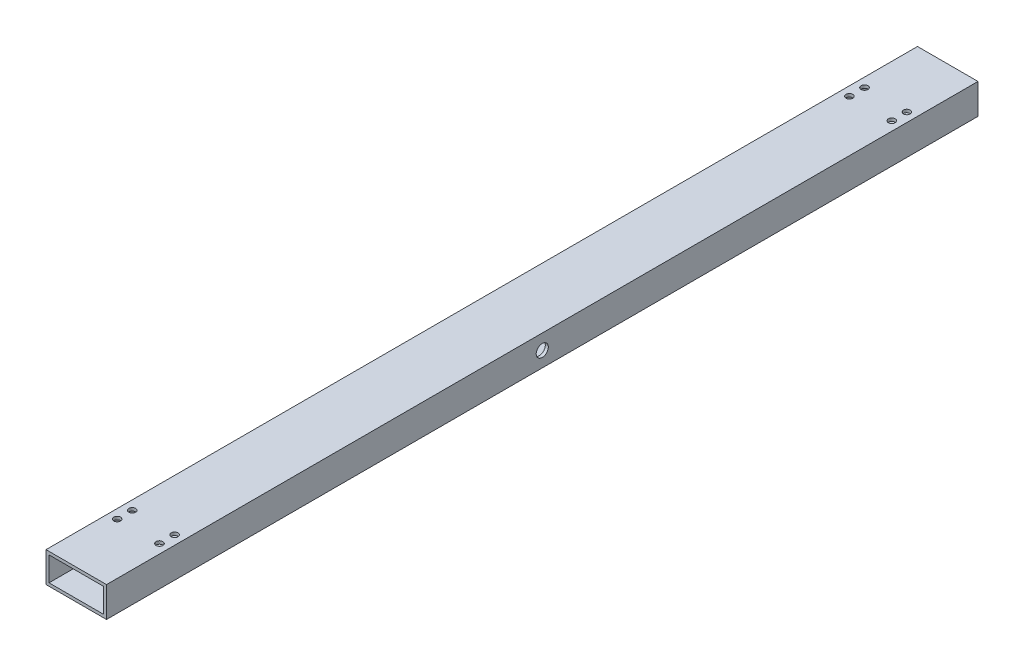
SolidWorks part; units mm, degrees
ref_plane "Front Plane" through (0, 0, 0) normal (0, 0, 1) x (1, 0, 0)
ref_plane "Top Plane" through (0, 0, 0) normal (0, 1, 0) x (1, 0, 0)
ref_plane "Right Plane" through (0, 0, 0) normal (1, 0, 0) x (0, 0, -1)
sketch "Sketch1" plane through (0, 0, 0) normal (0, 0, 1) x (1, 0, 0)
  line L0 (31.75, 0) -> (28.575, 0) construction
  line L1 (-31.75, 0) -> (31.75, 0) construction
  line L2 (0, 15.875) -> (0, -15.875)
  point P7 (0, 0)
  dimension "Width" = 63.5
  dimension "Wall Thickness" = 3.175
  dimension "Height" = 31.75
sketch "Sketch2" plane through (0, 0, 0) normal (1, 0, 0) x (0, 0, -1)
  line L0 (457.2, 0) -> (-457.2, 0)
  point P4 (0, 0)
  dimension "Length" = 914.4
sketch "Sketch3" plane through (0, 0, 0) normal (0, 0, 1) x (1, 0, 0)
  line L0 (0, 12.7) -> (0, 15.875) construction
  line L1 (-31.75, 15.875) -> (31.75, 15.875)
  line L2 (-31.75, 15.875) -> (-31.75, -15.875)
  line L3 (-31.75, -15.875) -> (31.75, -15.875)
  line L4 (31.75, 15.875) -> (31.75, -15.875)
  line L5 (-31.75, 15.875) -> (31.75, -15.875) construction
  line L6 (-31.75, -15.875) -> (31.75, 15.875) construction
  line L7 (-28.575, 12.7) -> (28.575, 12.7)
  line L8 (-28.575, 12.7) -> (-28.575, -12.7)
  line L9 (-28.575, -12.7) -> (28.575, -12.7)
  line L10 (28.575, 12.7) -> (28.575, -12.7)
  line L11 (-28.575, 12.7) -> (28.575, -12.7) construction
  line L12 (-28.575, -12.7) -> (28.575, 12.7) construction
  line L13 (31.75, 0) -> (28.575, 0) construction
  line L14 (31.75, 0) -> (28.575, 0) construction
  point P0 (0, 0)
  point P8 (0, 0)
extrude "Boss-Extrude1" add sketch "Sketch3" along normal up to vertex (457.2 mm away) and the other way up to vertex (457.2 mm away) up to point (0, 0, 457.2) other way up to point (0, 0, -457.2)
sketch "Sketch4" plane through (0, 0, 0) normal (0, 0, 1) x (1, 0, 0)
  line L0 (31.75, -15.875) -> (28.575, -15.875) construction
  line L1 (31.75, -15.875) -> (31.75, 15.875) construction
  line L2 (28.575, -12.7) -> (28.575, 12.7) construction
  line L3 (-31.75, -15.875) -> (31.75, -15.875) construction
sketch "Sketch5" plane through (0, -15.875, 0) normal (0, -1, 0) x (1, 0, 0)
  line L1 (-28.575, 384.175) -> (28.575, 384.175)
  line L2 (-28.575, 384.175) -> (-28.575, 400.05)
  line L3 (-28.575, 400.05) -> (28.575, 400.05)
  line L4 (28.575, 384.175) -> (28.575, 400.05)
  line L5 (-28.575, 384.175) -> (28.575, 400.05) construction
  line L6 (-28.575, 400.05) -> (28.575, 384.175) construction
  line L7 (-31.75, 457.2) -> (31.75, 457.2) construction
  line L8 (-31.75, 0) -> (31.75, 0) construction
  line L9 (-31.75, 457.2) -> (-31.75, -457.2) construction
  line L10 (31.75, 457.2) -> (31.75, -457.2) construction
  circle A0 centre (-22.225, 392.1125) radius 3.5719
  circle A1 centre (22.225, 392.1125) radius 3.5719
  circle A2 centre (22.225, -392.1125) radius 3.5719
  circle A3 centre (-22.225, -392.1125) radius 3.5719
  circle A4 centre (22.225, 376.2375) radius 3.5719
  circle A5 centre (-22.225, 376.2375) radius 3.5719
  circle A6 centre (22.225, -376.2375) radius 3.5719
  circle A7 centre (-22.225, -376.2375) radius 3.5719
  point P0 (0, 392.1125)
  dimension "D3" = 7.1437
  dimension "D4" = 7.1437
  dimension "D1" = 57.15
  dimension "D2" = 15.875
  dimension "D5" = 22.225
  dimension "D6" = 22.225
  dimension "D7" = 44.45
  dimension "D8" = 57.15
  dimension "D9" = 15.875
extrude "Cut-Extrude1" cut sketch "Sketch5" against normal through all contours A0 | A1 | A3 | A2 | A7 | A6 | A4 | A5
sketch "Sketch6" plane through (-31.75, 0, 0) normal (-1, 0, 0) x (0, 0, 1)
  circle A0 centre (0, 0) radius 6.35
  dimension "D1" = 12.7
extrude "Cut-Extrude2" cut sketch "Sketch6" against normal through all
sketch "Sketch7" plane through (0, 15.875, 0) normal (0, 1, 0) x (1, 0, 0)
  line L0 (0, 493.1857) -> (0, -485.0339)
  line L1 (-303.9468, 4.0759) -> (319.0859, 4.0759)
sketch "Sketch8" plane through (0, -15.875, 0) normal (0, -1, 0) x (1, 0, 0)
  line L0 (0, 0) -> (0, 203.2)
  line L4 (0, -493.1857) -> (0, 485.0339) construction
  point P2 (7.5696, -4.0759)
  point P3 (0, 0)
  point P9 (0, 203.2)
  dimension "D1" = 203.2
equation "\"actuatorMountingPointFromMiddle\"=10.126"
